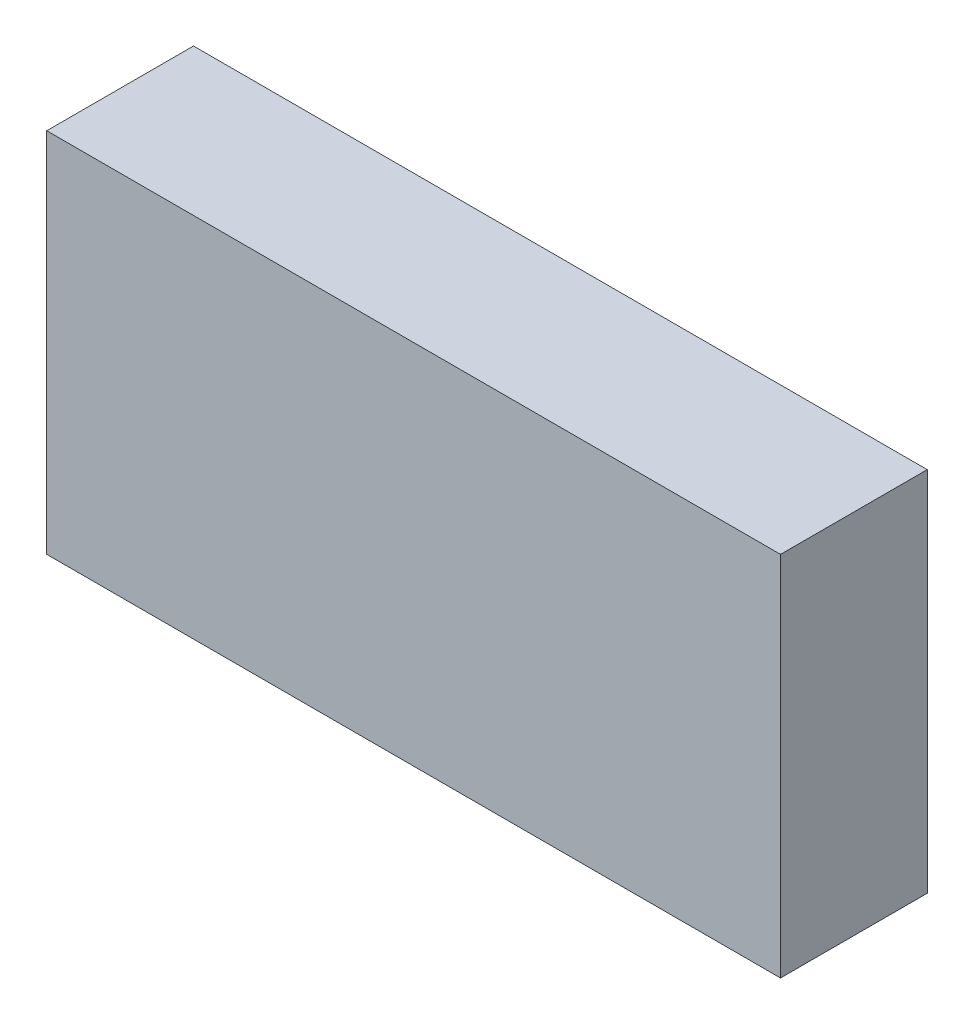
SolidWorks part; units mm, degrees
ref_plane "Alzado" through (0, 0, 0) normal (0, 0, 1) x (1, 0, 0)
ref_plane "Planta" through (0, 0, 0) normal (0, 1, 0) x (1, 0, 0)
ref_plane "Vista lateral" through (0, 0, 0) normal (1, 0, 0) x (0, 0, -1)
sketch "Croquis1" plane through (0, 0, 0) normal (0, 0, 1) x (1, 0, 0)
  line L1 (-50, 25) -> (50, 25)
  line L2 (-50, 25) -> (-50, -25)
  line L3 (-50, -25) -> (50, -25)
  line L4 (50, 25) -> (50, -25)
  point P7 (3.3418, -20.1954)
  dimension "D1" = 100
  dimension "D2" = 50
  dimension "D3" = 50
  dimension "D4" = 25
extrude "Saliente-Extruir1" add sketch "Croquis1" along normal blind 20
